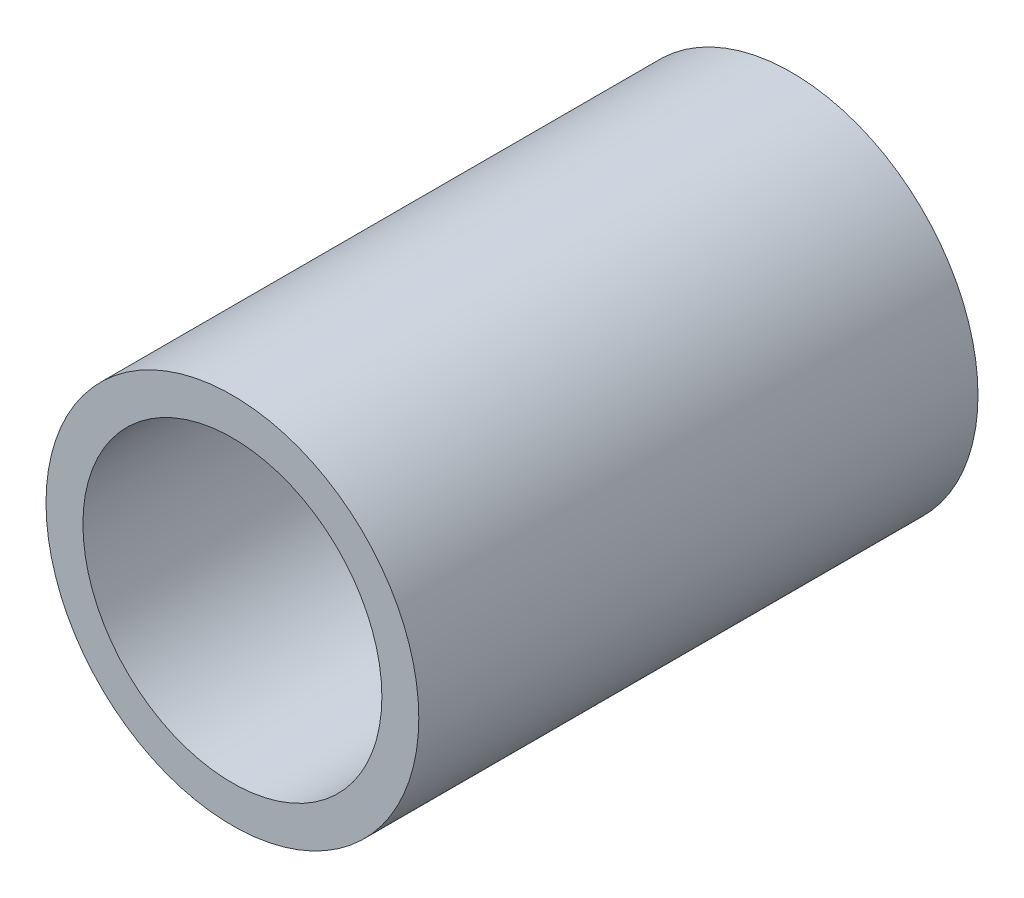
SolidWorks part; units mm, degrees
material "Commercial Bronze, UNS C22000 (90-10 Bronze)"
ref_plane "Front Plane" through (0, 0, 0) normal (0, 0, 1) x (1, 0, 0)
ref_plane "Top Plane" through (0, 0, 0) normal (0, 1, 0) x (1, 0, 0)
ref_plane "Right Plane" through (0, 0, 0) normal (1, 0, 0) x (0, 0, -1)
sketch "Sketch1" plane through (0, 0, 0) normal (0, 0, 1) x (1, 0, 0)
  circle A0 centre (0, 0) radius 5
  circle A1 centre (0, 0) radius 4.01
extrude "Sleeve" add sketch "Sketch1" along normal blind 15
